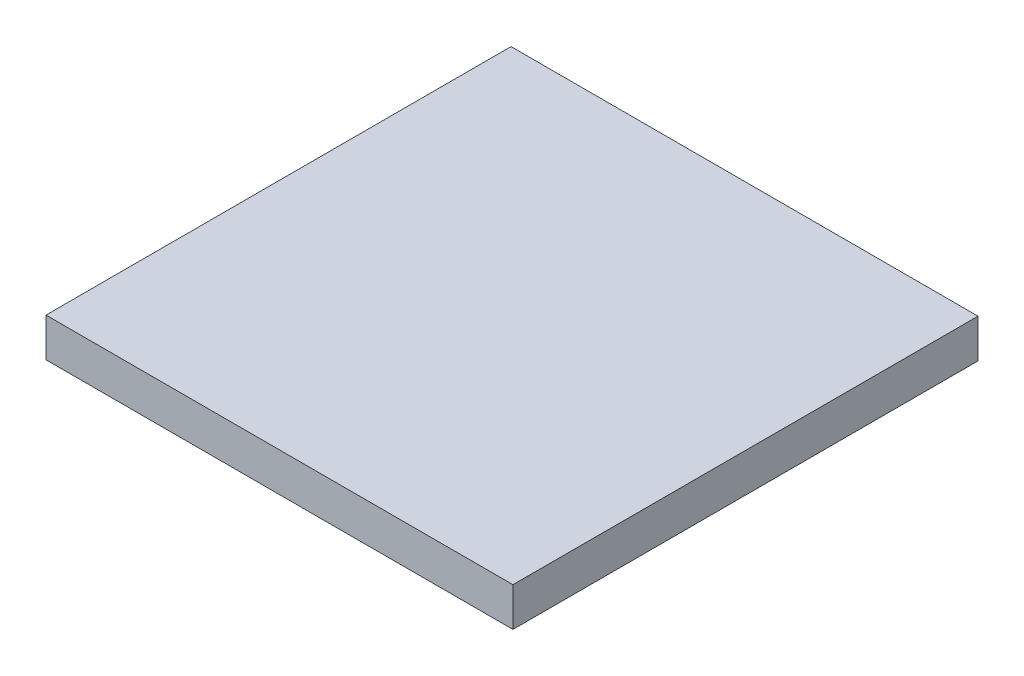
SolidWorks part; units mm, degrees
material "Custom Plastic"
ref_plane "X-Y Datum" through (0, 0, 0) normal (0, 0, 1) x (1, 0, 0)
ref_plane "X-Z Datum" through (0, 0, 0) normal (0, 1, 0) x (1, 0, 0)
ref_plane "Y-Z Datum" through (0, 0, 0) normal (1, 0, 0) x (0, 0, -1)
sketch "Sketch1" plane through (0, 0, 0) normal (0, 0, 1) x (1, 0, 0)
  line L1 (-153.0248, -12.7) -> (153.0248, -12.7)
  line L2 (-153.0248, -12.7) -> (-153.0248, 12.7)
  line L3 (-153.0248, 12.7) -> (153.0248, 12.7)
  line L4 (153.0248, -12.7) -> (153.0248, 12.7)
  line L5 (-153.0248, -12.7) -> (153.0248, 12.7) construction
  line L6 (-153.0248, 12.7) -> (153.0248, -12.7) construction
  point P0 (0, 0)
  dimension "D1" = 25.4
  dimension "D2" = 306.0497
extrude "Boss-Extrude1" add sketch "Sketch1" against normal blind 304.8
